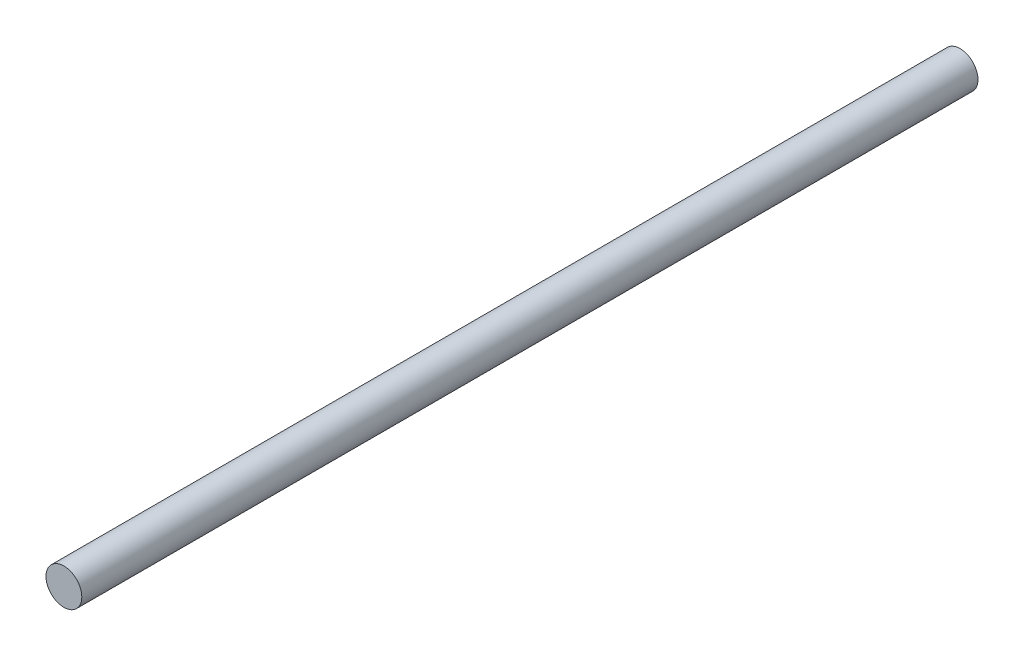
SolidWorks part; units mm, degrees
ref_plane "前视基准面" through (0, 0, 0) normal (0, 0, 1) x (1, 0, 0)
ref_plane "上视基准面" through (0, 0, 0) normal (0, 1, 0) x (1, 0, 0)
ref_plane "右视基准面" through (0, 0, 0) normal (1, 0, 0) x (0, 0, -1)
sketch "草图1" plane through (0, 0, 0) normal (0, 0, 1) x (1, 0, 0)
  circle A0 centre (0, 0) radius 4
  dimension "D1" = 8
extrude "凸台-拉伸1" add sketch "草图1" along normal blind 200
